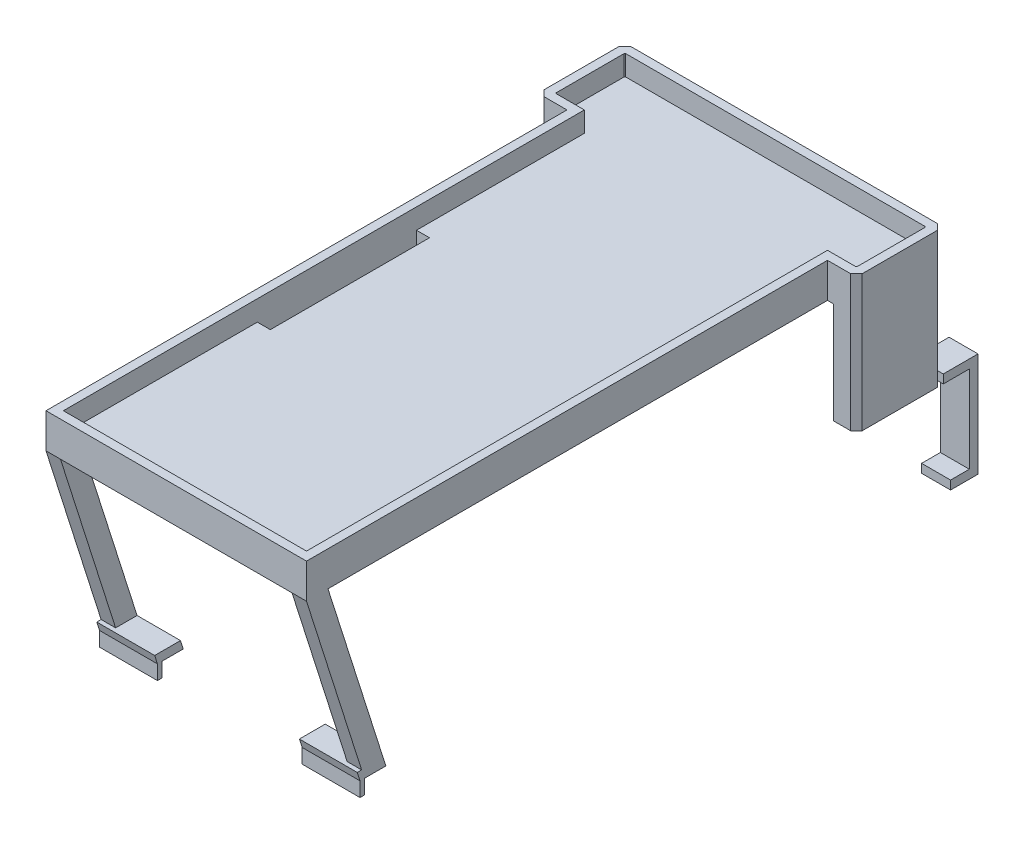
SolidWorks part; units mm, degrees
material "1060 Alloy"
ref_plane "Front Plane" through (0, 0, 0) normal (0, 0, 1) x (1, 0, 0)
ref_plane "Top Plane" through (0, 0, 0) normal (0, 1, 0) x (1, 0, 0)
ref_plane "Right Plane" through (0, 0, 0) normal (1, 0, 0) x (0, 0, -1)
sketch "Sketch1" plane through (0, 0, 0) normal (0, 1, 0) x (1, 0, 0)
  line L0 (-45, -30) -> (-45, -190)
  line L1 (-45, -190) -> (45, -190)
  line L2 (45, -190) -> (45, -30)
  line L3 (45, -30) -> (55, -30)
  line L4 (55, -30) -> (55, 0)
  line L5 (55, 0) -> (-55, 0)
  line L6 (-55, 0) -> (-55, -30)
  line L7 (-55, -30) -> (-45, -30)
  point P0 (0, 0)
  dimension "D1" = 90
  dimension "D2" = 190
  dimension "D3" = 110
  dimension "D4" = 10
  dimension "D5" = 30
extrude "Boss-Extrude1" add sketch "Sketch1" along normal blind 5
sketch "Sketch2" plane through (0, 5, 0) normal (0, 1, 0) x (1, 0, 0)
  line L0 (-45, -30) -> (-45, -190) construction
  line L1 (42, -140) -> (37.5, -140)
  line L2 (42, -140) -> (42, -85)
  line L3 (42, -85) -> (37.5, -85)
  line L4 (37.5, -140) -> (37.5, -85)
  line L5 (-37.5, -140) -> (-42, -140)
  line L6 (-37.5, -140) -> (-37.5, -85)
  line L7 (-37.5, -85) -> (-42, -85)
  line L8 (-42, -140) -> (-42, -85)
  line L9 (45, -190) -> (45, -30) construction
  line L10 (-45, -190) -> (45, -190) construction
  dimension "D1" = 3
  dimension "D2" = 3
  dimension "D3" = 4.5
  dimension "D4" = 50
  dimension "D5" = 55
extrude "Cut-Extrude1" cut sketch "Sketch2" against normal through all
sketch "Sketch3" plane through (0, 5, 0) normal (0, 1, 0) x (1, 0, 0)
  line L0 (55, 0) -> (-55, 0) construction
  line L1 (55, -30) -> (45, -30)
  line L2 (55, -30) -> (55, 0)
  line L3 (55, 0) -> (45, 0)
  line L4 (45, -30) -> (45, 0)
  line L5 (-45, -30) -> (-45, -190) construction
  line L6 (-55, -30) -> (-45, -30)
  line L7 (-55, -30) -> (-55, 0)
  line L8 (-55, 0) -> (-45, 0)
  line L9 (-45, -30) -> (-45, 0)
  line L10 (45, -190) -> (45, -30) construction
extrude "Boss-Extrude2" add sketch "Sketch3" against normal blind 35 from surface at -5 starting at face at (39.75, 0, 112.5)
chamfer "Chamfer1" distance 2 8 edges at (55, -15, 30) (45, -17.5, 30) (-45, -17.5, 30) (-55, -15, 30) (-55, -15, 0) (-45, -17.5, 0) (45, -17.5, 0) (55, -15, 0)
sketch "Sketch5" plane through (0, 0, 190) normal (0, 0, 1) x (1, 0, 0)
  line L4 (-45, 0) -> (45, 0)
  line L5 (45, 0) -> (45, 5)
  line L6 (45, 5) -> (-45, 5)
  line L7 (-45, 5) -> (-45, 0)
  line L8 (-45, 0) -> (45, 0)
  line L9 (45, 0) -> (45, 5)
  line L10 (45, 5) -> (-45, 5)
  line L11 (-45, 5) -> (-45, 0)
  dimension "D1" = 0
extrude "Boss-Extrude3" add sketch "Sketch5" along normal blind 20
sketch "Sketch8" plane through (-45, 0, 0) normal (-1, 0, 0) x (0, 0, 1)
  line L0 (202.5799, 0) -> (182.5799, -63)
  line L1 (30, 0) -> (210, 0) construction
  line L2 (190, -63) -> (175.1598, -63) construction
  line L3 (182.5799, -63) -> (190, -63)
  line L4 (190, -63) -> (210, 0)
  line L5 (210, 0) -> (202.5799, 0)
extrude "Boss-Extrude4" add sketch "Sketch8" against normal blind 5 contours L5 L0 L3 L4
sketch "Sketch9" plane through (-40, 0, 0) normal (1, 0, 0) x (0, 0, -1)
  line L0 (-190.9524, -60) -> (-183.5323, -60)
  line L1 (-190, -63) -> (-210, 0) construction
  line L2 (-202.5799, 0) -> (-182.5799, -63) construction
  line L3 (-183.5323, -60) -> (-182.5799, -63)
  line L4 (-190, -63) -> (-175.1598, -63) construction
  line L5 (-182.5799, -63) -> (-190, -63)
  line L6 (-190, -63) -> (-190.9524, -60)
  dimension "D1" = 3
extrude "Boss-Extrude5" add sketch "Sketch9" along normal blind 15 contours L0 L3 L5 L6
sketch "Sketch10" plane through (-45, 0, 0) normal (-1, 0, 0) x (0, 0, 1)
  line L0 (190, -68) -> (190, -63)
  line L1 (190, -63) -> (190.9524, -60)
  line L2 (190, -63) -> (210, 0) construction
  line L3 (190.9524, -60) -> (192.4524, -60)
  line L4 (192.4524, -60) -> (191.5, -63)
  line L5 (191.5, -63) -> (191.5, -68)
  line L6 (191.5, -68) -> (190, -68)
  dimension "D1" = 1.5
extrude "Boss-Extrude6" add sketch "Sketch10" against normal up to surface (20 mm away) up to face at (-25, -61.5, 186.7661)
mirror "Mirror1" about plane through (0, 0, 0) normal (1, 0, 0) of "Boss-Extrude6", "Boss-Extrude5", "Boss-Extrude4"
sketch "Sketch11" plane through (0, 5, 0) normal (0, 1, 0) x (1, 0, 0)
  line L24 (42, -27) -> (51.7574, -27)
  line L25 (51.7574, -27) -> (52, -26.7574)
  line L26 (52, -26.7574) -> (52, -3.2426)
  line L27 (52, -3.2426) -> (51.7574, -3)
  line L28 (51.7574, -3) -> (-51.7574, -3)
  line L29 (-51.7574, -3) -> (-52, -3.2426)
  line L30 (-52, -3.2426) -> (-52, -26.7574)
  line L31 (-52, -26.7574) -> (-51.7574, -27)
  line L32 (-51.7574, -27) -> (-42, -27)
  line L33 (-42, -27) -> (-42, -207)
  line L34 (-42, -207) -> (42, -207)
  line L35 (42, -207) -> (42, -27)
  line L36 (42, -27) -> (51.7574, -27)
  line L37 (51.7574, -27) -> (52, -26.7574)
  line L38 (52, -26.7574) -> (52, -3.2426)
  line L39 (52, -3.2426) -> (51.7574, -3)
  line L40 (51.7574, -3) -> (-51.7574, -3)
  line L41 (-51.7574, -3) -> (-52, -3.2426)
  line L42 (-52, -3.2426) -> (-52, -26.7574)
  line L43 (-52, -26.7574) -> (-51.7574, -27)
  line L44 (-51.7574, -27) -> (-42, -27)
  line L45 (-42, -27) -> (-42, -207)
  line L46 (-42, -207) -> (42, -207)
  line L47 (42, -207) -> (42, -27)
  line L48 (45, -30) -> (53, -30)
  line L49 (53, -30) -> (55, -28)
  line L50 (55, -28) -> (55, -2)
  line L51 (55, -2) -> (53, 0)
  line L52 (53, 0) -> (-53, 0)
  line L53 (-53, 0) -> (-55, -2)
  line L54 (-55, -2) -> (-55, -28)
  line L55 (-55, -28) -> (-53, -30)
  line L56 (-53, -30) -> (-45, -30)
  line L57 (-45, -30) -> (-45, -210)
  line L58 (-45, -210) -> (45, -210)
  line L59 (45, -210) -> (45, -30)
  line L60 (45, -30) -> (53, -30)
  line L61 (53, -30) -> (55, -28)
  line L62 (55, -28) -> (55, -2)
  line L63 (55, -2) -> (53, 0)
  line L64 (53, 0) -> (-53, 0)
  line L65 (-53, 0) -> (-55, -2)
  line L66 (-55, -2) -> (-55, -28)
  line L67 (-55, -28) -> (-53, -30)
  line L68 (-53, -30) -> (-45, -30)
  line L69 (-45, -30) -> (-45, -210)
  line L70 (-45, -210) -> (45, -210)
  line L71 (45, -210) -> (45, -30)
  line M25 (42, -85) -> (42, -140)
  line M31 (-42, -140) -> (-42, -85)
  line M33 (45, -30) -> (53, -30)
  line M34 (53, -30) -> (55, -28)
  line M35 (55, -28) -> (55, -2)
  line M36 (55, -2) -> (53, 0)
  line M37 (53, 0) -> (-53, 0)
  line M38 (-53, 0) -> (-55, -2)
  line M39 (-55, -2) -> (-55, -28)
  line M40 (-55, -28) -> (-53, -30)
  line M41 (-53, -30) -> (-45, -30)
  line M42 (-45, -30) -> (-45, -210)
  line M43 (-45, -210) -> (45, -210)
  line M44 (45, -210) -> (45, -30)
  dimension "D1" = 3
  dimension "D2" = 0
extrude "Boss-Extrude7" add sketch "Sketch11" along normal blind 7 contours L47 L46 L45 L44 L43 L42 L41 L40 L39 L38 L37 L36 M44 M33 M34 M35 M36 M37 M38 M39 M40 M41 M42 M43 M31 M25
sketch "Sketch12" plane through (55, 0, 0) normal (1, 0, 0) x (0, 0, -1)
  line L0 (0, -32) -> (12, -32)
  line L1 (0, 12) -> (0, -35) construction
  line L2 (12, -32) -> (12, -68)
  line L3 (12, -68) -> (2.5184, -68)
  line L4 (2.5184, -68) -> (2.5184, -65)
  line L5 (2.5184, -65) -> (9, -65)
  line L6 (9, -65) -> (9, -35)
  line L7 (9, -35) -> (0, -35)
  line L8 (0, -32) -> (0, -35)
  dimension "D1" = 33
  dimension "D2" = 3
  dimension "D3" = 3
  dimension "D4" = 3
  dimension "D5" = 12
extrude "Boss-Extrude8" add sketch "Sketch12" against normal up to surface (10 mm away) contours L8 L7 L6 L5 L4 L3 L2 L0 up to face at (45, -17.5, 15)
